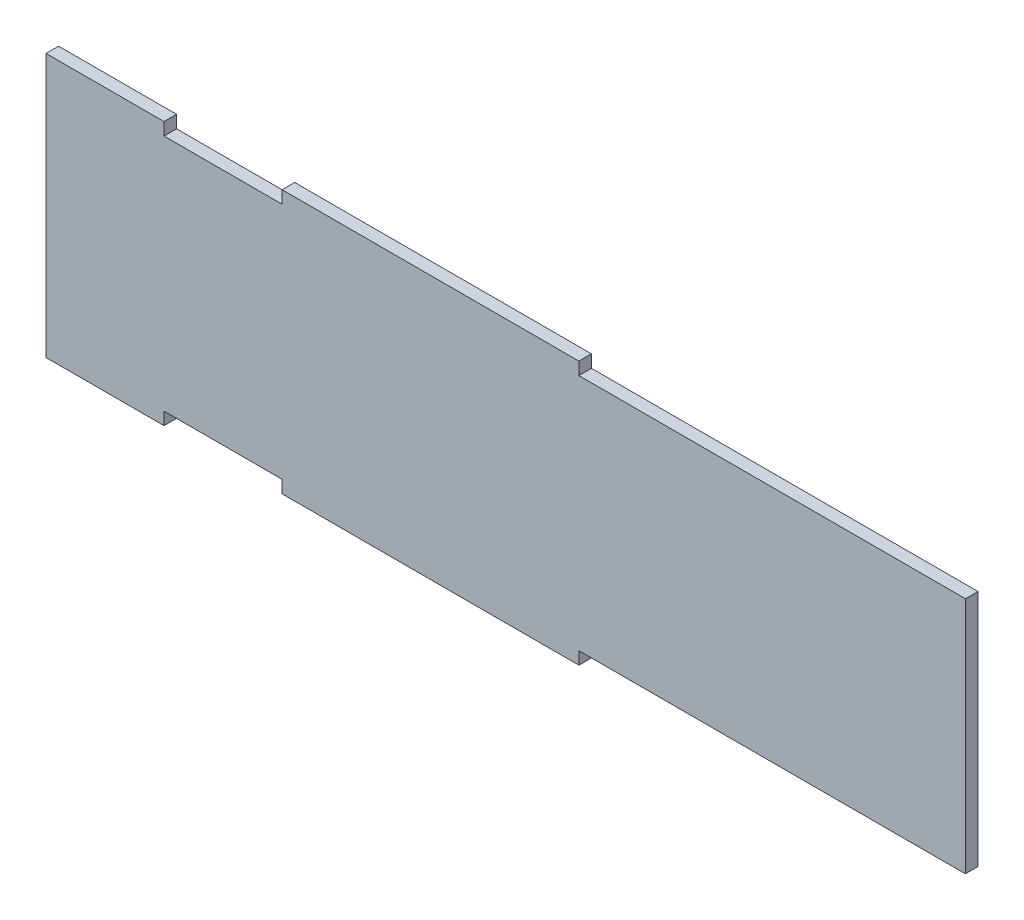
SolidWorks part; units mm, degrees
ref_plane "Front Plane" through (0, 0, 0) normal (0, 0, 1) x (1, 0, 0)
ref_plane "Top Plane" through (0, 0, 0) normal (0, 1, 0) x (1, 0, 0)
ref_plane "Right Plane" through (0, 0, 0) normal (1, 0, 0) x (0, 0, -1)
sketch "Sketch1" plane through (0, 0, 0) normal (0, 0, 1) x (1, 0, 0)
  line L0 (-146.9136, 56.5278) -> (-146.9136, 51.4224) construction
  line L1 (-197.866, -56.6802) -> (197.866, -56.6802)
  line L2 (-197.866, -56.6802) -> (-197.866, 56.6802)
  line L3 (-197.866, 56.6802) -> (197.866, 56.6802)
  line L4 (197.866, -56.6802) -> (197.866, 56.6802)
  line L5 (-197.866, -56.6802) -> (197.866, 56.6802) construction
  line L6 (-197.866, 56.6802) -> (197.866, -56.6802) construction
  line L7 (-147.066, 56.6802) -> (-96.266, 56.6802)
  line L8 (-147.066, 56.6802) -> (-147.066, 51.27)
  line L9 (-147.066, 51.27) -> (-96.266, 51.27)
  line L10 (-96.266, 56.6802) -> (-96.266, 51.27)
  line L11 (31.496, 56.6802) -> (197.866, 56.6802)
  line L12 (31.496, 56.6802) -> (31.496, 51.27)
  line L13 (31.496, 51.27) -> (197.866, 51.27)
  line L14 (197.866, 56.6802) -> (197.866, 51.27)
  line L15 (-146.9136, 51.4224) -> (-96.4184, 51.4224) construction
  line L16 (-96.4184, 56.5278) -> (-96.4184, 51.4224) construction
  line L17 (-146.9136, 56.5278) -> (-96.4184, 56.5278)
  line L18 (31.6484, 56.5278) -> (31.6484, 51.4224) construction
  line L19 (31.6484, 51.4224) -> (197.7136, 51.4224) construction
  line L20 (197.7136, 56.5278) -> (197.7136, 51.4224) construction
  line L21 (31.6484, 56.5278) -> (197.7136, 56.5278)
  line L22 (197.866, 0) -> (-197.866, 0)
  line L23 (197.7136, -56.5278) -> (197.7136, -51.4224) construction
  line L24 (31.6484, -51.4224) -> (197.7136, -51.4224) construction
  line L25 (31.6484, -56.5278) -> (31.6484, -51.4224) construction
  line L26 (-96.4184, -56.5278) -> (-96.4184, -51.4224) construction
  line L27 (-146.9136, -51.4224) -> (-96.4184, -51.4224) construction
  line L28 (-146.9136, -56.5278) -> (-146.9136, -51.4224) construction
  line L29 (31.6484, -56.5278) -> (197.7136, -56.5278)
  line L30 (-146.9136, -56.5278) -> (-96.4184, -56.5278)
  line L31 (197.866, -56.6802) -> (197.866, -51.27)
  line L32 (31.496, -51.27) -> (197.866, -51.27)
  line L33 (31.496, -56.6802) -> (31.496, -51.27)
  line L34 (31.496, -56.6802) -> (197.866, -56.6802)
  line L35 (-96.266, -56.6802) -> (-96.266, -51.27)
  line L36 (-147.066, -51.27) -> (-96.266, -51.27)
  line L37 (-147.066, -56.6802) -> (-147.066, -51.27)
  line L38 (-147.066, -56.6802) -> (-96.266, -56.6802)
  point P0 (0, 0)
  dimension "D2" = 395.732
  dimension "D3" = 50.8
  dimension "D4" = 0
  dimension "D5" = 5.4102
  dimension "D6" = 5.4102
  dimension "D7" = 50.8
  dimension "D8" = 229.362
  dimension "D9" = 5.4102
  dimension "D12" = 102.5401
  dimension "D10" = 0.1524
  dimension "D11" = 0.1524
extrude "Boss-Extrude1" add sketch "Sketch1" along normal blind 5.4102 contours L22 L4 L3 L14 L13 L12 L10 L9 L8 L2 | L1 L37 L36 L35 L33 L32 L31 L4 L22 L2
